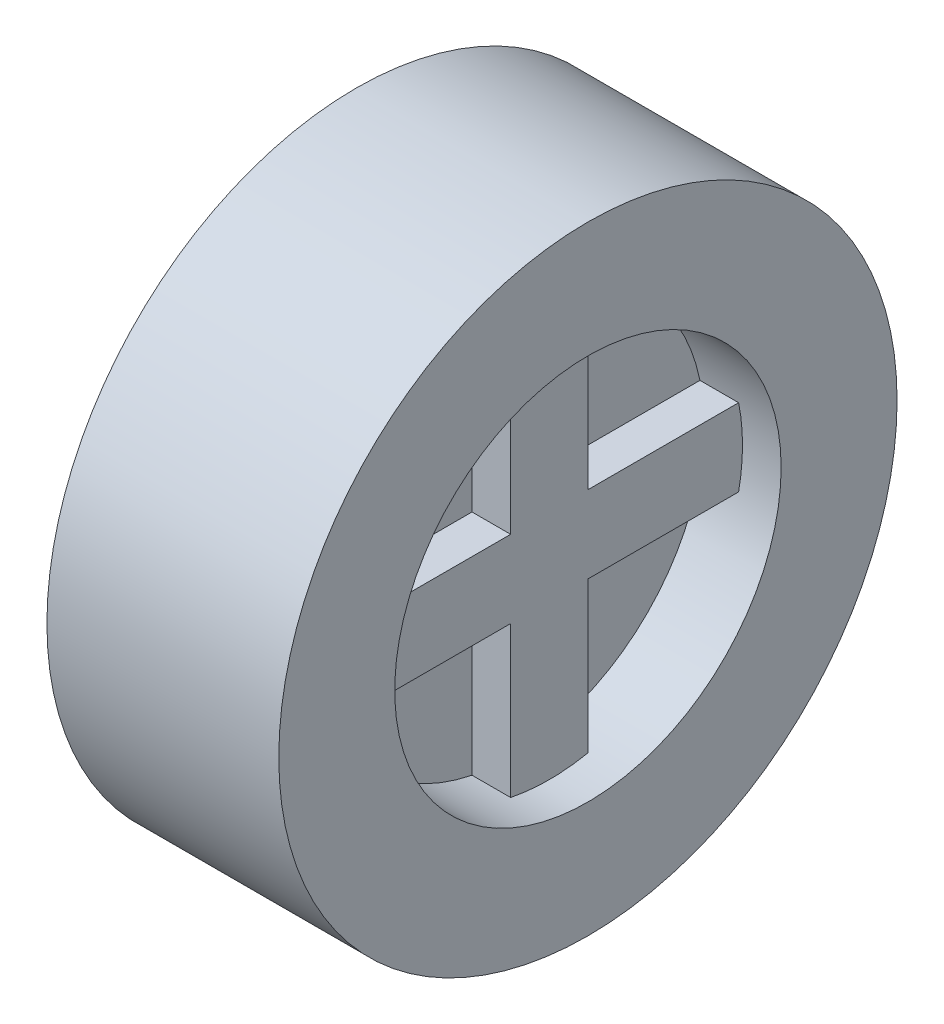
SolidWorks part; units mm, degrees
material "1.6569 (17NiCrMoS6-4)"
ref_plane "前视基准面" through (0, 0, 0) normal (0, 0, 1) x (1, 0, 0)
ref_plane "上视基准面" through (0, 0, 0) normal (0, 1, 0) x (1, 0, 0)
ref_plane "右视基准面" through (0, 0, 0) normal (1, 0, 0) x (0, 0, -1)
sketch "草图1" plane through (0, 0, 0) normal (1, 0, 0) x (0, 0, -1)
  circle A0 centre (0, 0) radius 4
  circle A1 centre (0, 0) radius 2.5
extrude "凸台-拉伸1" add sketch "草图1" along normal blind 3 contours A0 A1
sketch "草图2" plane through (3, 0, 0) normal (1, 0, 0) x (0, 0, -1)
  circle A0 centre (0, 0) radius 2.5
extrude "切除-拉伸1" cut sketch "草图2" against normal blind 1
sketch "草图3" plane through (0, 0, 0) normal (-1, 0, 0) x (0, 0, 1)
  circle A0 centre (0, 0) radius 2.5
extrude "切除-拉伸2" cut sketch "草图3" against normal blind 1
sketch "草图4" plane through (2, 0, 0) normal (1, 0, 0) x (0, 0, -1)
  line L0 (-0.5, -0.5) -> (-0.5, -2.4495)
  line L1 (0.5, -0.5) -> (0.5, -2.4495)
  line L2 (0.5, 2.4495) -> (0.5, 0.5)
  line L3 (-0.5, 2.4495) -> (-0.5, 0.5)
  line L6 (0.5, 0.5) -> (2.4495, 0.5)
  line L7 (0.5, -0.5) -> (2.4495, -0.5)
  line L8 (-0.5, 0.5) -> (-2.4495, 0.5)
  line L9 (-0.5, -0.5) -> (-2.4495, -0.5)
  arc A2 (0.5, 2.4495) -> (-0.5, 2.4495) centre (0, 0) ccw
  arc A3 (-2.4495, 0.5) -> (-2.4495, -0.5) centre (0, 0) ccw
  arc A4 (-0.5, -2.4495) -> (0.5, -2.4495) centre (0, 0) ccw
  arc A5 (2.4495, -0.5) -> (2.4495, 0.5) centre (0, 0) ccw
extrude "凸台-拉伸2" add sketch "草图4" along normal blind 0.5
